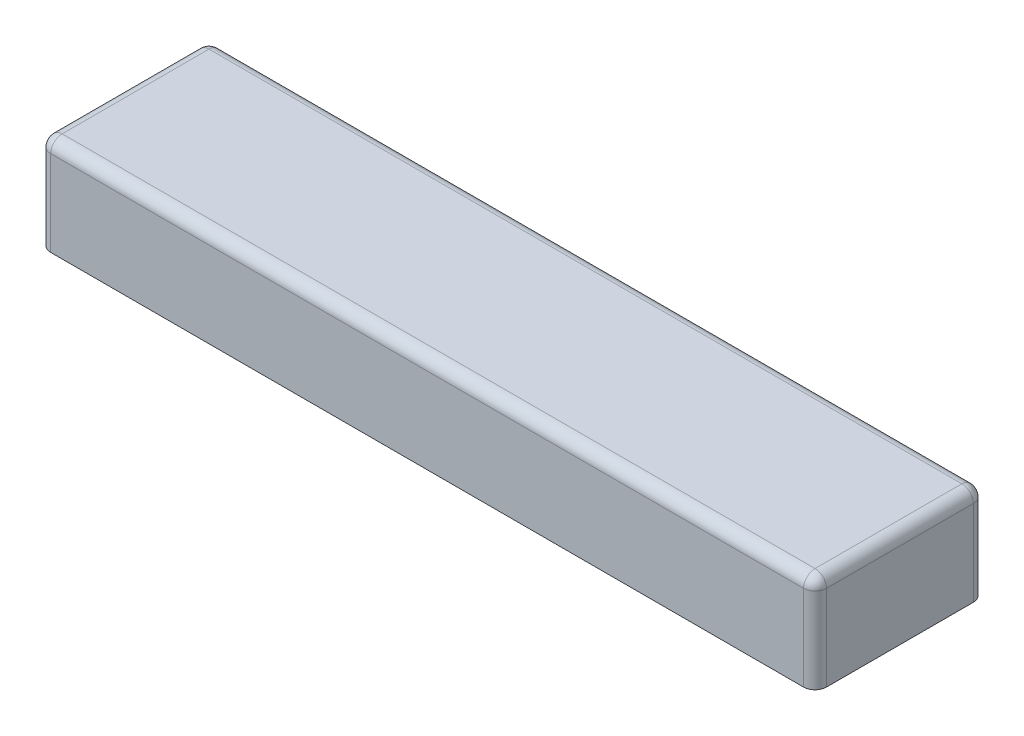
SolidWorks part; units mm, degrees
ref_plane "Front Plane" through (0, 0, 0) normal (0, 0, 1) x (1, 0, 0)
ref_plane "Top Plane" through (0, 0, 0) normal (0, 1, 0) x (1, 0, 0)
ref_plane "Right Plane" through (0, 0, 0) normal (1, 0, 0) x (0, 0, -1)
sketch "Sketch1" plane through (0, 0, 0) normal (0, 1, 0) x (1, 0, 0)
  line L1 (0, 0) -> (203.2, 0)
  line L2 (0, 0) -> (0, 44.45)
  line L3 (0, 44.45) -> (203.2, 44.45)
  line L4 (203.2, 0) -> (203.2, 44.45)
  dimension "D1" = 203.2
  dimension "D2" = 44.45
extrude "Boss-Extrude1" add sketch "Sketch1" along normal blind 25.4
fillet "Fillet1" radius 3 8 edges at (101.6, 25.4, -44.45) (203.2, 25.4, -22.225) (101.6, 25.4, 0) (0, 25.4, -22.225) (0, 12.7, -44.45) (203.2, 12.7, -44.45) (203.2, 12.7, 0) (0, 12.7, 0)
